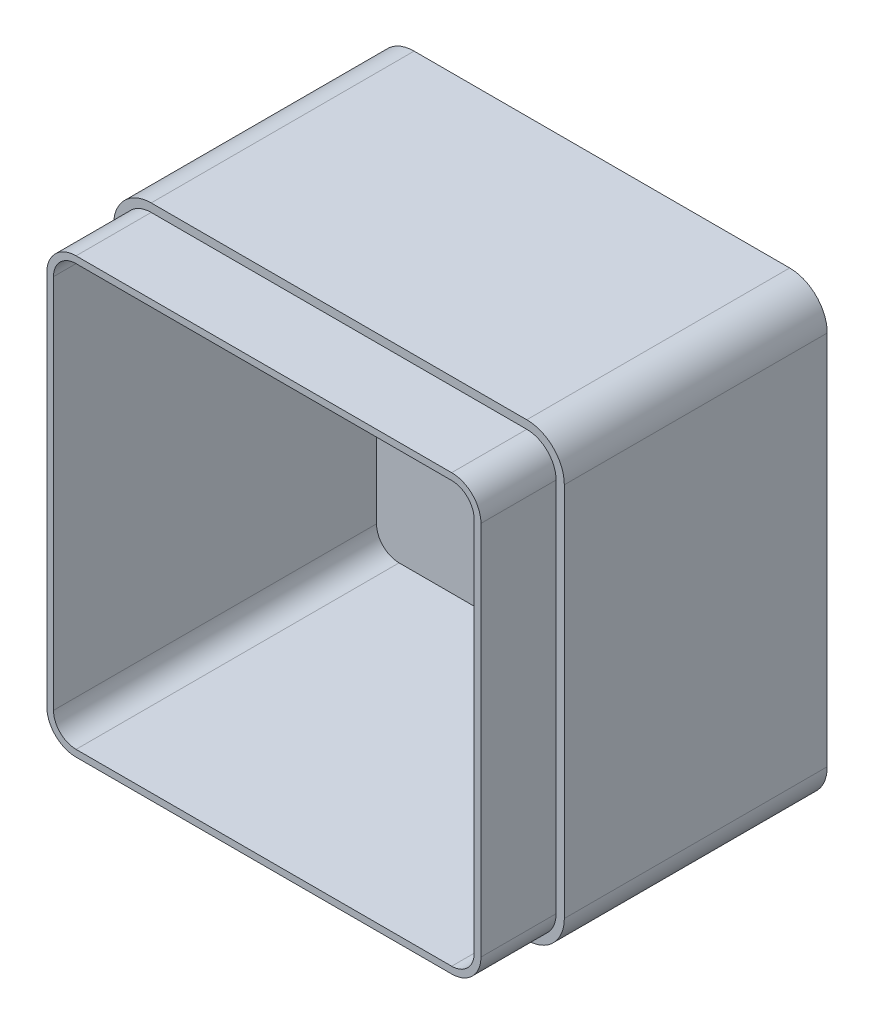
SolidWorks part; units mm, degrees
ref_plane "Front Plane" through (0, 0, 0) normal (0, 0, 1) x (1, 0, 0)
ref_plane "Top Plane" through (0, 0, 0) normal (0, 1, 0) x (1, 0, 0)
ref_plane "Right Plane" through (0, 0, 0) normal (1, 0, 0) x (0, 0, -1)
sketch "Sketch2" plane through (0, 0, 0) normal (0, 0, 1) x (1, 0, 0)
  line L1 (0, 0) -> (120, 0)
  line L2 (0, 0) -> (0, 120)
  line L3 (0, 120) -> (120, 120)
  line L4 (120, 0) -> (120, 120)
  dimension "D1" = 120
  dimension "D2" = 120
extrude "Boss-Extrude1" add sketch "Sketch2" along normal blind 90
fillet "Fillet1" radius 10 4 edges at (0, 0, 45) (120, 0, 45) (120, 120, 45) (0, 120, 45)
shell "Shell1" thickness 4
sketch "Sketch3" plane through (0, 0, 90) normal (0, 0, 1) x (1, 0, 0)
  line L0 (2.2, 110) -> (2.2, 10)
  line L1 (10, 2.2) -> (110, 2.2)
  line L2 (117.8, 10) -> (117.8, 110)
  line L3 (110, 117.8) -> (10, 117.8)
  line L4 (0, 110) -> (0, 10)
  line L5 (10, 0) -> (110, 0)
  line L6 (120, 10) -> (120, 110)
  line L7 (110, 120) -> (10, 120)
  line L8 (0, 110) -> (0, 10)
  line L9 (10, 0) -> (110, 0)
  line L10 (120, 10) -> (120, 110)
  line L11 (110, 120) -> (10, 120)
  arc A0 (2.2, 10) -> (10, 2.2) centre (10, 10) ccw
  arc A1 (110, 2.2) -> (117.8, 10) centre (110, 10) ccw
  arc A2 (117.8, 110) -> (110, 117.8) centre (110, 110) ccw
  arc A3 (10, 117.8) -> (2.2, 110) centre (10, 110) ccw
  arc A4 (0, 10) -> (10, 0) centre (10, 10) ccw
  arc A5 (110, 0) -> (120, 10) centre (110, 10) ccw
  arc A6 (120, 110) -> (110, 120) centre (110, 110) ccw
  arc A7 (10, 120) -> (0, 110) centre (10, 110) ccw
  arc A8 (0, 10) -> (10, 0) centre (10, 10) ccw
  arc A9 (110, 0) -> (120, 10) centre (110, 10) ccw
  arc A10 (120, 110) -> (110, 120) centre (110, 110) ccw
  arc A11 (10, 120) -> (0, 110) centre (10, 110) ccw
  dimension "D1" = 0
  dimension "D2" = 2.2
extrude "Cut-Extrude1" cut sketch "Sketch3" against normal blind 20
extrude "Cut-Extrude2" cut sketch "Sketch4" against normal through all
sketch "Sketch4" plane through (92.803, -8.4469, 120) normal (0, 0, 1) x (1, 0, 0)
  circle A0 centre (-73.753, 109.3969) radius 6.35
equation "\"PrintFitAllowance\" = 0.2mm"
equation "\"D2@Sketch3\"=\"PrintFitAllowance\"+2.00mm"
